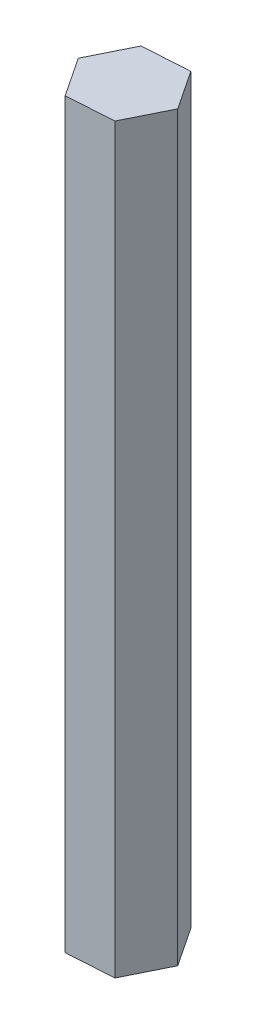
SolidWorks part; units mm, degrees
ref_plane "Front Plane" through (0, 0, 0) normal (0, 0, 1) x (1, 0, 0)
ref_plane "Top Plane" through (0, 0, 0) normal (0, 1, 0) x (1, 0, 0)
ref_plane "Right Plane" through (0, 0, 0) normal (1, 0, 0) x (0, 0, -1)
sketch "Sketch1" plane through (0, 0, 0) normal (0, 1, 0) x (1, 0, 0)
  line L1 (3.2599, 6.5678) -> (-4.0579, 6.1071)
  line L2 (-4.0579, 6.1071) -> (-7.3179, -0.4607)
  line L3 (-7.3179, -0.4607) -> (-3.2599, -6.5678)
  line L4 (-3.2599, -6.5678) -> (4.0579, -6.1071)
  line L5 (4.0579, -6.1071) -> (7.3179, 0.4607)
  line L6 (7.3179, 0.4607) -> (3.2599, 6.5678)
  circle A0 centre (0, 0) radius 6.35 construction
  dimension "D1" = 12.7
extrude "Boss-Extrude1" add sketch "Sketch1" along normal blind 116.078
